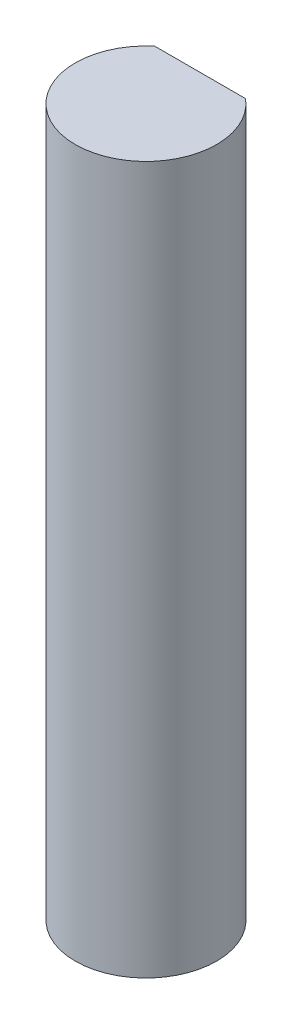
SolidWorks part; units mm, degrees
material "1023 Листовая углеродистая сталь (SS)"
ref_plane "Спереди" through (0, 0, 0) normal (0, 0, 1) x (1, 0, 0)
ref_plane "Сверху" through (0, 0, 0) normal (0, 1, 0) x (1, 0, 0)
ref_plane "Справа" through (0, 0, 0) normal (1, 0, 0) x (0, 0, -1)
sketch "Эскиз1" plane through (0, 0, 0) normal (0, 1, 0) x (1, 0, 0)
  circle A0 centre (0, 0) radius 3
  dimension "D1" = 6
extrude "Бобышка-Вытянуть1" add sketch "Эскиз1" along normal blind 30
sketch "Эскиз2" plane through (0, 30, 0) normal (0, 1, 0) x (1, 0, 0)
  line L1 (-2.5, 4.3) -> (2.5, 4.3)
  line L2 (-2.5, 4.3) -> (-2.5, 2.3)
  line L3 (-2.5, 2.3) -> (2.5, 2.3)
  line L4 (2.5, 4.3) -> (2.5, 2.3)
  line L5 (-2.5, 4.3) -> (2.5, 2.3) construction
  line L6 (-2.5, 2.3) -> (2.5, 4.3) construction
  point P0 (0, 3.3)
  dimension "D1" = 2.3
  dimension "D2" = 2
  dimension "D3" = 5
extrude "Вырез-Вытянуть1" cut sketch "Эскиз2" against normal through all
